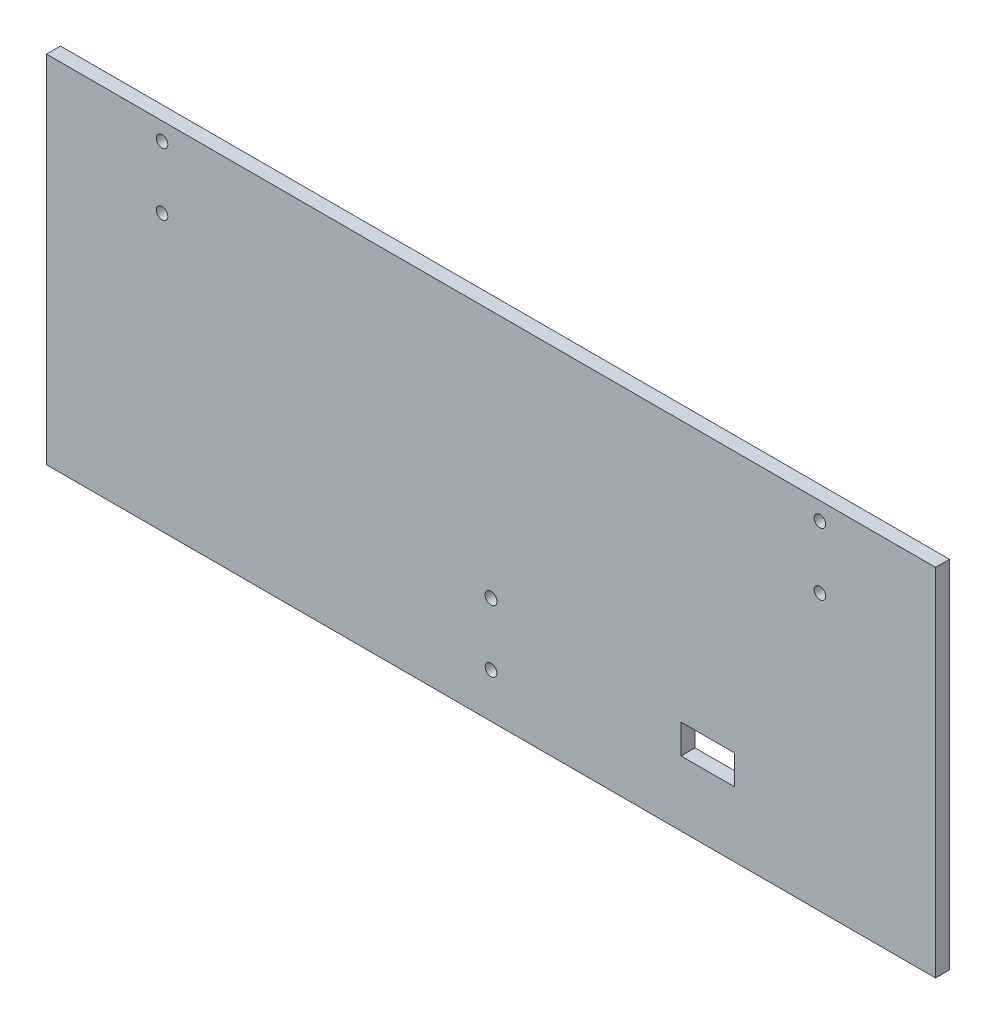
SolidWorks part; units mm, degrees
ref_plane "Front Plane" through (0, 0, 0) normal (0, 0, 1) x (1, 0, 0)
ref_plane "Top Plane" through (0, 0, 0) normal (0, 1, 0) x (1, 0, 0)
ref_plane "Right Plane" through (0, 0, 0) normal (1, 0, 0) x (0, 0, -1)
sketch "Sketch1" plane through (0, 0, 0) normal (0, 0, 1) x (1, 0, 0)
  line L0 (0, 0) -> (254, 0)
  line L1 (0, 0) -> (0, 101.6)
  line L3 (254, 101.6) -> (254, 0)
  line L4 (33.02, 101.6046) -> (0, 101.6) construction
  line L6 (254, 101.6) -> (220.98, 101.6) construction
  line L7 (33.02, 101.6046) -> (39.624, 101.6046) construction
  line L8 (39.624, 101.6046) -> (39.624, 65.5366) construction
  line L9 (39.624, 65.5366) -> (26.416, 65.5366) construction
  line L10 (26.416, 65.5366) -> (26.416, 101.6046) construction
  line L11 (26.416, 101.6046) -> (33.02, 101.6046) construction
  line L12 (33.02, 101.6046) -> (33.02, 78.7446) construction
  line L22 (220.98, 101.6) -> (220.98, 78.74) construction
  line L23 (220.98, 101.6) -> (220.98, 65.532) construction
  line L24 (220.98, 101.6) -> (214.376, 101.6) construction
  line L30 (220.98, 65.532) -> (220.98, 101.6) construction
  line L32 (220.98, 78.74) -> (220.98, 96.52) construction
  line L33 (127, 4.064) -> (133.604, 4.064) construction
  line L34 (133.604, 4.064) -> (133.604, 40.132) construction
  line L35 (133.604, 40.132) -> (120.396, 40.132) construction
  line L36 (120.396, 40.132) -> (120.396, 4.064) construction
  line L37 (120.396, 4.064) -> (127, 4.064) construction
  line L38 (127, 40.132) -> (127, 30.48) construction
  line L39 (127, 30.48) -> (127, 12.7) construction
  line L40 (214.376, 101.6) -> (214.376, 65.532) construction
  line L41 (214.376, 65.532) -> (220.98, 65.532) construction
  line L42 (220.98, 65.532) -> (227.584, 65.532) construction
  line L43 (227.584, 65.532) -> (227.584, 101.6) construction
  line L44 (0, 101.6) -> (254, 101.6)
  line L46 (181.2856, 26.9716) -> (196.5764, 26.9716)
  line L47 (181.2856, 26.9716) -> (181.2856, 18.5896)
  line L48 (181.2856, 18.5896) -> (196.5764, 18.5896)
  line L49 (196.5764, 26.9716) -> (196.5764, 18.5896)
  line L50 (181.2856, 26.9716) -> (196.5764, 18.5896) construction
  line L51 (181.2856, 18.5896) -> (196.5764, 26.9716) construction
  circle A2 centre (33.02, 96.5246) radius 1.651
  circle A3 centre (33.02, 78.7446) radius 1.651
  circle A6 centre (127, 30.48) radius 1.6891
  circle A7 centre (127, 12.7) radius 1.6637
  circle A8 centre (220.98, 96.52) radius 1.651
  circle A9 centre (220.98, 78.74) radius 1.651
  point P11 (188.931, 22.7806)
  point P27 (127, 0)
  dimension "D1" = 254
  dimension "D5" = 17.78
  dimension "D8" = 3.302
  dimension "D9" = 33.02
  dimension "D14" = 3.3782
  dimension "D2" = 101.6
  dimension "D3" = 36.068
  dimension "D4" = 13.208
  dimension "D6" = 33.02
  dimension "D7" = 17.78
  dimension "D10" = 36.068
  dimension "D11" = 9.652
  dimension "D12" = 13.208
  dimension "D13" = 36.068
  dimension "D15" = 17.78
  dimension "D16" = 22.86
  dimension "D17" = 12.7
  dimension "D18" = 22.86
  dimension "D19" = 15.2908
  dimension "D20" = 8.382
extrude "Boss-Extrude1" add sketch "Sketch1" along normal blind 4
